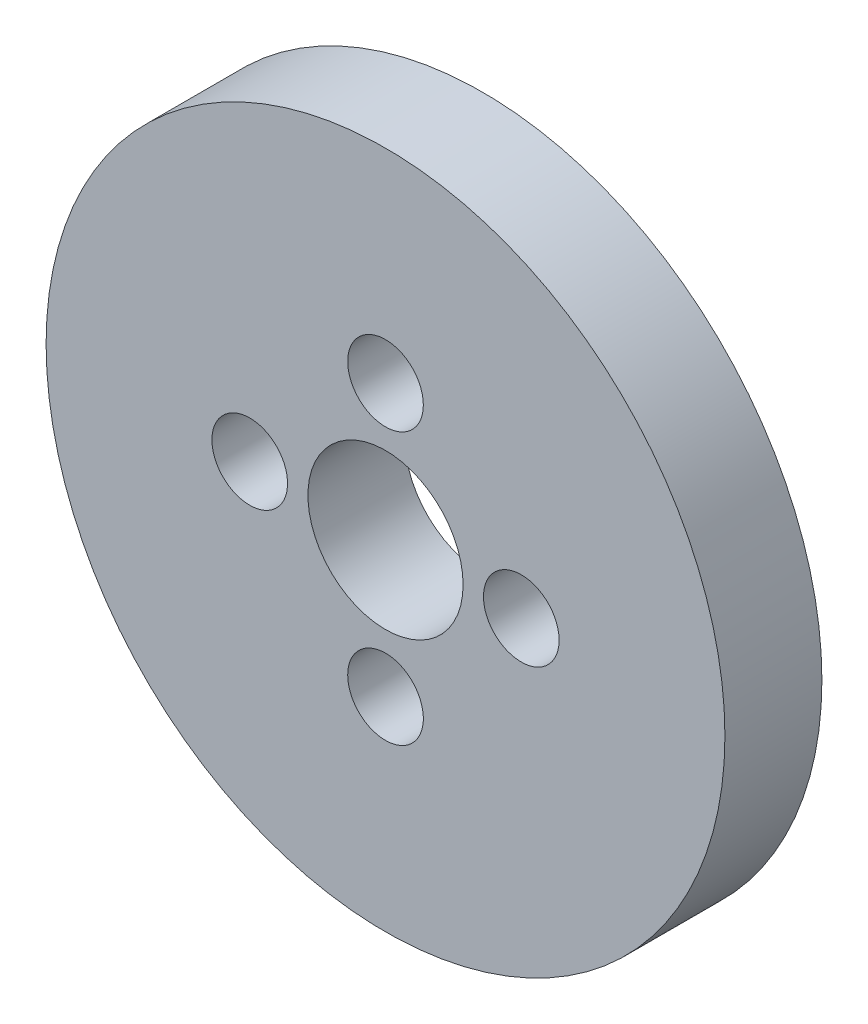
SolidWorks part; units mm, degrees
ref_plane "Front Plane" through (0, 0, 0) normal (0, 0, 1) x (1, 0, 0)
ref_plane "Top Plane" through (0, 0, 0) normal (0, 1, 0) x (1, 0, 0)
ref_plane "Right Plane" through (0, 0, 0) normal (1, 0, 0) x (0, 0, -1)
sketch "Sketch1" plane through (0, 0, 0) normal (0, 0, 1) x (1, 0, 0)
  line L0 (-7, 0) -> (7, 0) construction
  line L1 (0, 7) -> (0, -7) construction
  circle A0 centre (0, 0) radius 17.5
  circle A1 centre (0, 0) radius 4
  circle A2 centre (7, 0) radius 1.95
  circle A3 centre (0, 7) radius 1.95
  circle A4 centre (0, -7) radius 1.95
  circle A5 centre (-7, 0) radius 1.95
  point P12 (0, 0)
  point P13 (0, 0)
  dimension "D1" = 8
  dimension "D2" = 35
  dimension "D3" = 3.9
  dimension "D4" = 14
  dimension "D5" = 14
extrude "Boss-Extrude1" add sketch "Sketch1" along normal blind 5
